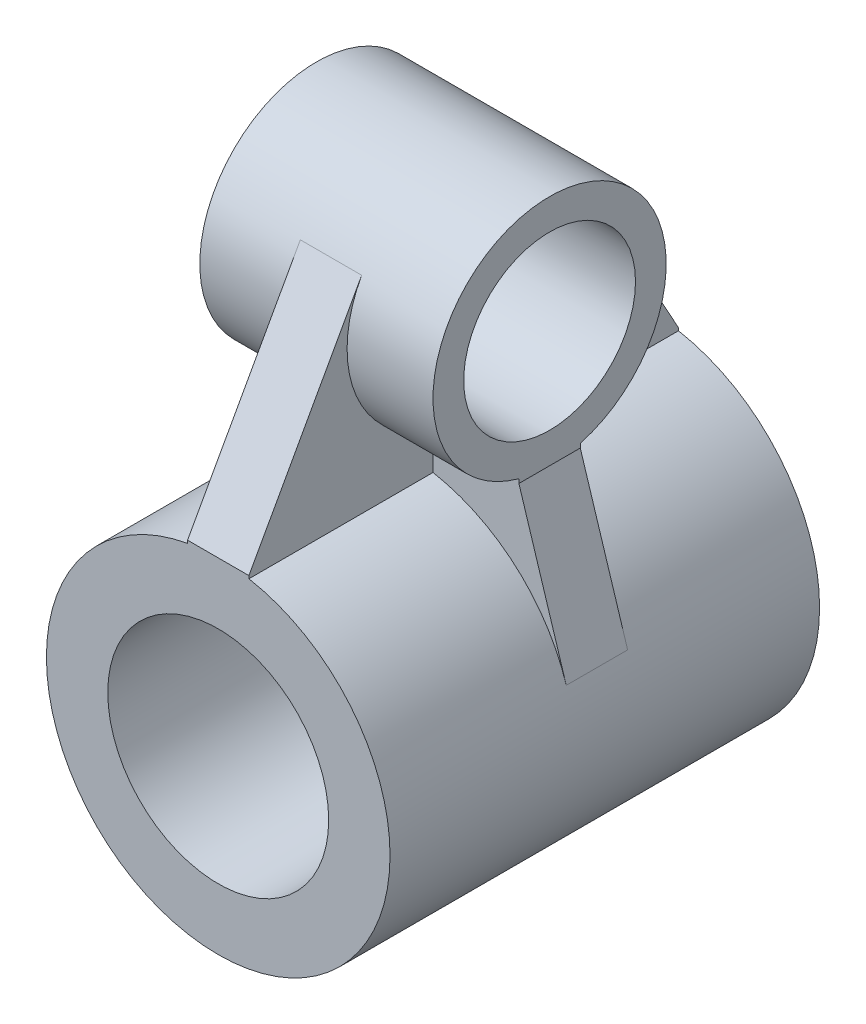
SolidWorks part; units mm, degrees
ref_plane "Front Plane" through (0, 0, 0) normal (0, 0, 1) x (1, 0, 0)
ref_plane "Top Plane" through (0, 0, 0) normal (0, 1, 0) x (1, 0, 0)
ref_plane "Right Plane" through (0, 0, 0) normal (1, 0, 0) x (0, 0, -1)
sketch "Sketch1" plane through (0, 0, 0) normal (0, 0, 1) x (1, 0, 0)
  circle A0 centre (0, 0) radius 14
  circle A1 centre (0, 0) radius 9
  dimension "D1" = 28
  dimension "D2" = 18
extrude "Boss-Extrude1" add sketch "Sketch1" along normal mid plane 35
sketch "Sketch5" plane through (0, 0, 0) normal (1, 0, 0) x (0, 0, -1)
  line L0 (0, 0) -> (0, 26) construction
  circle A0 centre (0, 26) radius 7
  circle A1 centre (0, 26) radius 9.5
  dimension "D2" = 14
  dimension "D3" = 19
  dimension "D1" = 26
extrude "Boss-Extrude2" add sketch "Sketch5" along normal mid plane 19 separate body
sketch "Sketch6" plane through (0, 0, 0) normal (1, 0, 0) x (0, 0, -1)
  line L0 (-8.3118, 30.6005) -> (-17.5, 14)
  line L1 (-17.5, 14) -> (0, 14)
  line L2 (17.5, 14) -> (-17.5, 14) construction
  line L3 (0, 14) -> (0, 16.5)
  circle A0 centre (0, 26) radius 9.5 construction
  arc A1 (-8.3118, 30.6005) -> (0, 16.5) centre (0, 26) ccw
extrude "Boss-Extrude3" add sketch "Sketch6" along normal mid plane 5
sketch "Sketch7" plane through (0, 14, 0) normal (0, -1, 0) x (1, 0, 0)
  line L4 (-2.5, 17.5) -> (-2.5, 0)
  line L5 (-2.5, 0) -> (2.5, 0)
  line L6 (2.5, 0) -> (2.5, 17.5)
  line L7 (2.5, 17.5) -> (-2.5, 17.5)
  line L8 (-2.5, 17.5) -> (-2.5, 0)
  line L9 (-2.5, 0) -> (2.5, 0)
  line L10 (2.5, 0) -> (2.5, 17.5)
  line L11 (2.5, 17.5) -> (-2.5, 17.5)
  dimension "D1" = 0
extrude "Boss-Extrude4" add sketch "Sketch7" along normal up to next
sketch "Sketch8" plane through (0, 0, 0) normal (1, 0, 0) x (0, 0, -1)
  line L0 (8.3118, 30.6005) -> (17.5, 14)
  line L2 (0, 0) -> (0, 26) construction
  line L3 (17.5, 14) -> (0, 14) construction
  line L4 (0, 14) -> (0, 16.5)
  line L5 (0, 14) -> (0, 13.6503)
  line L6 (0, 13.6503) -> (17.5, 13.6503)
  line L7 (17.5, 13.6503) -> (17.5, 14)
  circle A0 centre (0, 26) radius 9.5 construction
  circle A1 centre (0, 26) radius 9.5
extrude "Boss-Extrude5" add sketch "Sketch8" along normal mid plane 5 contours A1 L4 L5 L6 L7 L0
sketch "Sketch9" plane through (0, 0, 0) normal (0, 0, 1) x (1, 0, 0)
  line L1 (0, 14) -> (0, 16.5)
  line L2 (0, 16.5) -> (0, 35.5) construction
  line L4 (-13.3592, 4.1871) -> (-9.5, 16.5)
  line L5 (0, 17.5) -> (-9.5, 17.5)
  line L6 (-9.5, 17.5) -> (-9.5, 16.5)
  line L7 (0, 17.5) -> (0, 16.5)
  circle A0 centre (0, 0) radius 14 construction
  circle A2 centre (0, 0) radius 14
extrude "Boss-Extrude9" add sketch "Sketch9" along normal mid plane 5 contours A2 L1 L7 L5 L6 L4
mirror "Mirror9" about plane through (0, 0, 0) normal (1, 0, 0) of "Boss-Extrude9"
